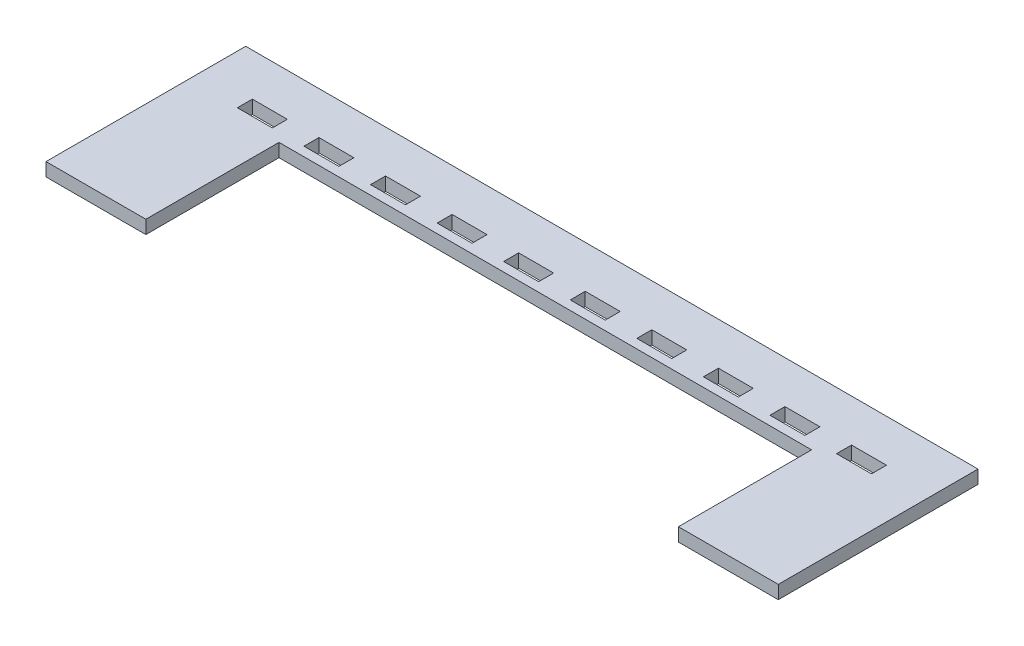
SolidWorks part; units mm, degrees
ref_plane "Спереди" through (0, 0, 0) normal (0, 0, 1) x (1, 0, 0)
ref_plane "Сверху" through (0, 0, 0) normal (0, 1, 0) x (1, 0, 0)
ref_plane "Справа" through (0, 0, 0) normal (1, 0, 0) x (0, 0, -1)
sketch "Эскиз1" plane through (0, 0, 0) normal (0, 1, 0) x (1, 0, 0)
  line L0 (-135, -16.7889) -> (-135, -56.7889)
  line L1 (55, -16.7889) -> (-105, -16.7889)
  line L2 (85, -16.7889) -> (85, 3.2111)
  line L3 (85, 3.2111) -> (-135, 3.2111)
  line L4 (-135, -16.7889) -> (-135, 3.2111)
  line L5 (-135, -56.7889) -> (-105, -56.7889)
  line L6 (-105, -56.7889) -> (-105, -16.7889)
  line L7 (-25, -16.7889) -> (-25, 56.3847) construction
  line L8 (85, -56.7889) -> (55, -56.7889)
  line L9 (55, -56.7889) -> (55, -16.7889)
  line L10 (85, -16.7889) -> (85, -56.7889)
  point P0 (0, 0)
  dimension "D1" = 220
  dimension "D2" = 60
  dimension "D3" = 20
  dimension "D4" = 30
extrude "Бобышка-Вытянуть1" add sketch "Эскиз1" along normal blind 4
sketch "Эскиз2" plane through (0, 0, 0) normal (0, 1, 0) x (1, 0, 0)
  line L1 (-105, -11.7889) -> (-44.1885, -11.7889) construction
  line L3 (-120.25, -14.0389) -> (-109.75, -14.0389)
  line L4 (-120.25, -14.0389) -> (-120.25, -9.5389)
  line L5 (-120.25, -9.5389) -> (-109.75, -9.5389)
  line L6 (-109.75, -14.0389) -> (-109.75, -9.5389)
  line L7 (-120.25, -14.0389) -> (-109.75, -9.5389) construction
  line L8 (-120.25, -9.5389) -> (-109.75, -14.0389) construction
  line L9 (-135, 3.2111) -> (-135, -56.7889) construction
  line L10 (-100.25, -9.5389) -> (-89.75, -9.5389)
  line L11 (-100.25, -14.0389) -> (-100.25, -9.5389)
  line L12 (-100.25, -14.0389) -> (-89.75, -14.0389)
  line L13 (-89.75, -14.0389) -> (-89.75, -9.5389)
  line L14 (-80.25, -9.5389) -> (-69.75, -9.5389)
  line L15 (-80.25, -14.0389) -> (-80.25, -9.5389)
  line L16 (-80.25, -14.0389) -> (-69.75, -14.0389)
  line L17 (-69.75, -14.0389) -> (-69.75, -9.5389)
  line L18 (-60.25, -9.5389) -> (-49.75, -9.5389)
  line L19 (-60.25, -14.0389) -> (-60.25, -9.5389)
  line L20 (-60.25, -14.0389) -> (-49.75, -14.0389)
  line L21 (-49.75, -14.0389) -> (-49.75, -9.5389)
  line L22 (-40.25, -9.5389) -> (-29.75, -9.5389)
  line L23 (-40.25, -14.0389) -> (-40.25, -9.5389)
  line L24 (-40.25, -14.0389) -> (-29.75, -14.0389)
  line L25 (-29.75, -14.0389) -> (-29.75, -9.5389)
  line L26 (-20.25, -9.5389) -> (-9.75, -9.5389)
  line L27 (-20.25, -14.0389) -> (-20.25, -9.5389)
  line L28 (-20.25, -14.0389) -> (-9.75, -14.0389)
  line L29 (-9.75, -14.0389) -> (-9.75, -9.5389)
  line L30 (-0.25, -9.5389) -> (10.25, -9.5389)
  line L31 (-0.25, -14.0389) -> (-0.25, -9.5389)
  line L32 (-0.25, -14.0389) -> (10.25, -14.0389)
  line L33 (10.25, -14.0389) -> (10.25, -9.5389)
  line L34 (19.75, -9.5389) -> (30.25, -9.5389)
  line L35 (19.75, -14.0389) -> (19.75, -9.5389)
  line L36 (19.75, -14.0389) -> (30.25, -14.0389)
  line L37 (30.25, -14.0389) -> (30.25, -9.5389)
  line L38 (39.75, -9.5389) -> (50.25, -9.5389)
  line L39 (39.75, -14.0389) -> (39.75, -9.5389)
  line L40 (39.75, -14.0389) -> (50.25, -14.0389)
  line L41 (50.25, -14.0389) -> (50.25, -9.5389)
  line L42 (59.75, -9.5389) -> (70.25, -9.5389)
  line L43 (59.75, -14.0389) -> (59.75, -9.5389)
  line L44 (59.75, -14.0389) -> (70.25, -14.0389)
  line L45 (70.25, -14.0389) -> (70.25, -9.5389)
  point P0 (-105, -11.7889)
  point P4 (-115, -11.7889)
  point P9 (0, 0)
  dimension "D1" = 5
  dimension "D2" = 4.5
  dimension "D3" = 10.5
  dimension "D4" = 14.75
  dimension "D5" = 10
extrude "Вырез-Вытянуть1" cut sketch "Эскиз2" along normal through all
